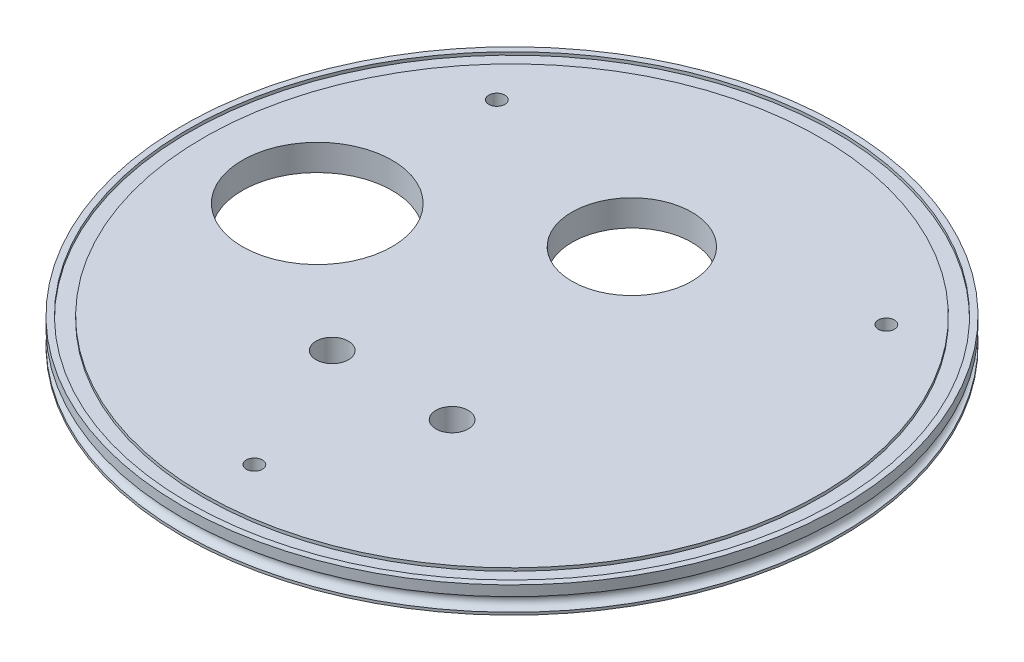
SolidWorks part; units mm, degrees
material "AISI 304"
ref_plane "Front Plane" through (0, 0, 0) normal (0, 0, 1) x (1, 0, 0)
ref_plane "Top Plane" through (0, 0, 0) normal (0, 1, 0) x (1, 0, 0)
ref_plane "Right Plane" through (0, 0, 0) normal (1, 0, 0) x (0, 0, -1)
sketch "Sketch1" plane through (0, 0, 0) normal (0, 0, 1) x (1, 0, 0)
  line L0 (0, 28.207) -> (0, -33.9706) construction
  line L1 (0, 0) -> (0, 11.1125)
  line L2 (0, 11.1125) -> (130.81, 11.1125)
  line L3 (139.7, 11.1125) -> (139.7, 6.7945)
  line L4 (139.7, 0) -> (127, 0)
  line L5 (139.7, 1.0795) -> (139.7, 0)
  line L6 (139.7, 11.1125) -> (137.16, 11.1125)
  line L7 (137.16, 11.1125) -> (137.16, 9.8425)
  line L8 (137.16, 9.8425) -> (130.81, 9.8425)
  line L9 (130.81, 9.8425) -> (130.81, 11.1125)
  line L10 (137.16, 11.1125) -> (139.7, 11.1125)
  line L11 (127, 0) -> (127, 2.54)
  line L12 (127, 2.54) -> (120.65, 2.54)
  line L13 (120.65, 2.54) -> (120.65, 0)
  line L14 (120.65, 0) -> (0, 0)
  arc A0 (139.7, 6.7945) -> (139.7, 1.0795) centre (139.7, 3.937) ccw
  dimension "D3" = 2.8575
  dimension "D2" = 11.1125
  dimension "D4" = 4.318
  dimension "D5" = 12.7
  dimension "D6" = 2.54
  dimension "D7" = 6.35
  dimension "D8" = 1.27
  dimension "D9" = 2.54
  dimension "D10" = 127
  dimension "D11" = 6.35
revolve "Revolve2" add sketch "Sketch1" angle 360 about L0
sketch "Sketch2" plane through (0, 11.1125, 0) normal (0, 1, 0) x (1, 0, 0)
  circle A0 centre (-25.4, -50.8) radius 6.858
  circle A1 centre (25.4, -50.8) radius 6.858
  point P4 (0, 0)
  dimension "D3" = 13.716
  dimension "D4" = 13.716
  dimension "D1" = 25.4
  dimension "D2" = 25.4
  dimension "D5" = 50.8
  dimension "D6" = 50.8
extrude "Cut-Extrude1" cut sketch "Sketch2" against normal through all
sketch "Sketch3" plane through (0, 11.1125, 0) normal (0, 1, 0) x (1, 0, 0)
  circle A0 centre (0, 50.8) radius 25.4
  circle A1 centre (-82.55, 0) radius 31.75
  circle A2 centre (25.4, -50.8) radius 6.858 construction
  point P6 (0, 0)
  dimension "D1" = 50.8
  dimension "D2" = 63.5
  dimension "D3" = 82.55
  dimension "D5" = 82.55
  dimension "D6" = 101.6
  dimension "D4" = 50.8
extrude "Cut-Extrude3" cut sketch "Sketch3" against normal through all
sketch "Sketch4" plane through (0, 11.1125, 0) normal (0, 1, 0) x (1, 0, 0)
  circle A0 centre (57.15, 0) radius 3.429
  circle A1 centre (-48.26, -31.75) radius 3.429
  circle A2 centre (-48.26, 31.75) radius 3.429
  point P2 (0, 0)
  dimension "D6" = 6.858
  dimension "D7" = 6.858
  dimension "D8" = 6.858
  dimension "D1" = 57.15
  dimension "D2" = 48.26
  dimension "D3" = 48.26
  dimension "D4" = 31.75
  dimension "D5" = 31.75
extrude "Cut-Extrude4" cut sketch "Sketch4" against normal blind 6.35 from offset 4.826 offset against normal yes
sketch "Sketch6" plane through (0, 11.1125, 0) normal (0, 1, 0) x (1, 0, 0)
  line L0 (0, -109.22) -> (0, 76.1273) construction
  line L1 (0, -109.22) -> (82.55, 76.1273) construction
  line L2 (82.55, 76.1273) -> (-82.55, 76.1273) construction
  line L3 (-82.55, 76.1273) -> (0, -109.22) construction
  circle A0 centre (0, -109.22) radius 3.429
  circle A1 centre (82.55, 76.1273) radius 3.429
  circle A2 centre (-82.55, 76.1273) radius 3.429
  circle A3 centre (0, 50.8) radius 25.4 construction
  circle A4 centre (25.4, -50.8) radius 6.858 construction
  dimension "D1" = 6.858
  dimension "D2" = 6.858
  dimension "D3" = 6.858
  dimension "D6" = 82.55
  dimension "D7" = 58.42
  dimension "D4" = 82.55
  dimension "D5" = 185.3473
extrude "Cut-Extrude6" cut sketch "Sketch6" against normal blind 6.35
